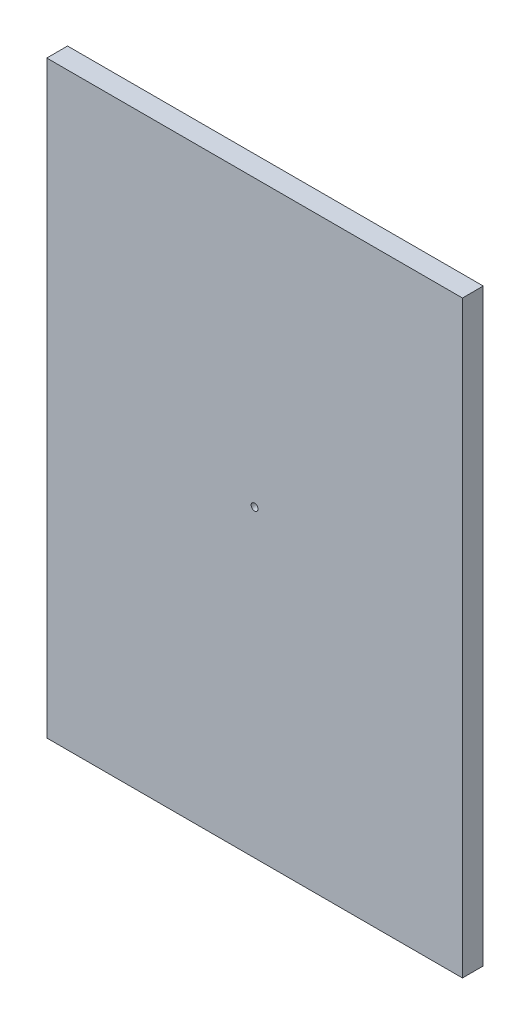
SolidWorks part; units mm, degrees
material "Glass"
ref_plane "Front Plane" through (0, 0, 0) normal (0, 0, 1) x (1, 0, 0)
ref_plane "Top Plane" through (0, 0, 0) normal (0, 1, 0) x (1, 0, 0)
ref_plane "Right Plane" through (0, 0, 0) normal (1, 0, 0) x (0, 0, -1)
sketch "Sketch1" plane through (0, 0, 0) normal (0, 0, 1) x (1, 0, 0)
  line L0 (30, -42.5) -> (30, -41.14) construction
  line L1 (0, 0) -> (60, 0)
  line L2 (0, 0) -> (0, -85)
  line L3 (0, -85) -> (60, -85)
  line L4 (60, 0) -> (60, -85)
  circle A0 centre (30, -42.5) radius 0.5
  circle A1 centre (30, -41.14) radius 0.5
  point P7 (60, -42.5)
  point P8 (30, 0)
  point P11 (0, 0)
  dimension "D3" = 1
  dimension "D1" = 60
  dimension "D2" = 85
  dimension "D4" = 1.36
extrude "Boss-Extrude1" add sketch "Sketch1" along normal blind 3
ref_plane "Plane1" through (30, 0, 0) normal (1, 0, 0) x (0, 0, -1)
sketch "Sketch2" plane through (30, 0, 0) normal (1, 0, 0) x (0, 0, -1)
  line L1 (-3, -42.5) -> (-8, -42.5) construction
  line L2 (-3, -41.14) -> (-215.132, 170.992) construction
  line L3 (-3, -41.14) -> (-8, -41.14) construction
  line L4 (-3, 0) -> (-3, -85) construction
  point P0 (-4.3036, -36.14)
  point P6 (0, 0)
  point P7 (0, 0)
  point P11 (0, 0)
  dimension "D1" = 5
  dimension "D3" = 45
  dimension "D4" = 300
equation "\"D4@Sketch1\"=1.36"
